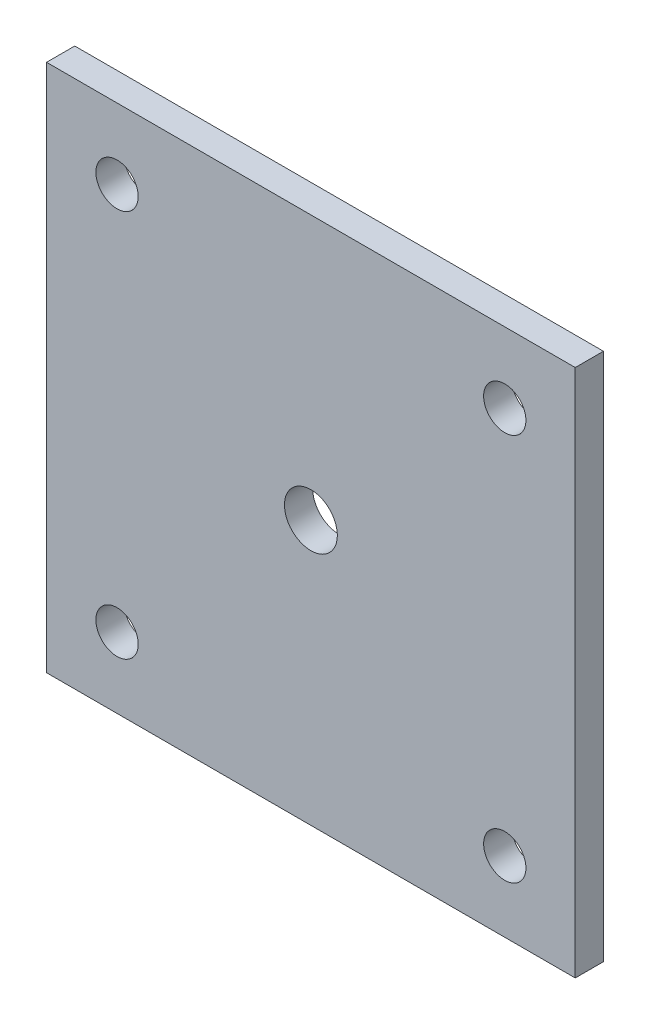
SolidWorks part; units mm, degrees
ref_plane "Front Plane" through (0, 0, 0) normal (1, 0, 0) x (0, 1, 0)
ref_plane "Top Plane" through (0, 0, 0) normal (0, 0, 1) x (0, 1, 0)
ref_plane "Right Plane" through (0, 0, 0) normal (0, 1, 0) x (-1, 0, 0)
sketch "Sketch1" plane through (0, 0, 0) normal (0, 0, 1) x (0, 1, 0)
  line L1 (-75, -75) -> (75, -75)
  line L2 (-75, -75) -> (-75, 75)
  line L3 (-75, 75) -> (75, 75)
  line L4 (75, -75) -> (75, 75)
  line L5 (-75, -75) -> (75, 75) construction
  line L6 (-75, 75) -> (75, -75) construction
  point P0 (0, 0)
  dimension "D1" = 150
  dimension "D2" = 150
extrude "Boss-Extrude1" add sketch "Sketch1" along normal blind 8
sketch "Sketch2" plane through (0, 0, 0) normal (0, 0, 1) x (0, 1, 0)
  line L0 (75, 75) -> (-75, 75) construction
  line L1 (-75, 75) -> (-75, -75) construction
  line L2 (75, -75) -> (75, 75) construction
  line L3 (-75, -75) -> (75, -75) construction
  circle A0 centre (-55, 55) radius 6
  circle A1 centre (55, 55) radius 6
  circle A2 centre (-55, -55) radius 6
  circle A3 centre (55, -55) radius 6
  dimension "D1" = 12
  dimension "D2" = 12
  dimension "D3" = 12
  dimension "D4" = 12
  dimension "D5" = 20
  dimension "D6" = 20
  dimension "D7" = 20
  dimension "D8" = 20
  dimension "D9" = 20
  dimension "D10" = 20
  dimension "D11" = 20
  dimension "D12" = 20
extrude "Cut-Extrude1" cut sketch "Sketch2" along normal through all
sketch "Sketch3" plane through (0, 0, 0) normal (0, 0, 1) x (0, 1, 0)
  circle A0 centre (0, 0) radius 7.5
  dimension "D1" = 15
extrude "Cut-Extrude2" cut sketch "Sketch3" along normal through all
